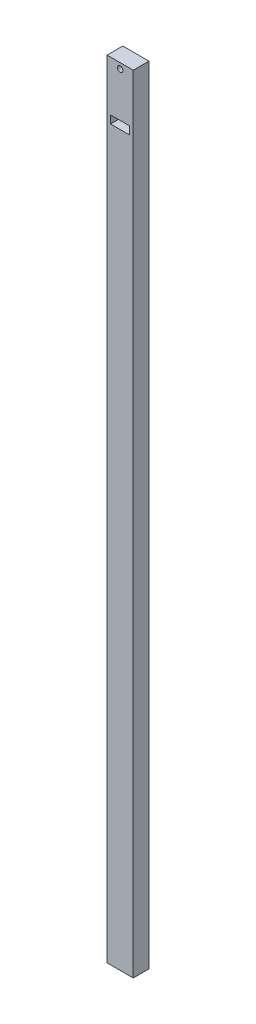
SolidWorks part; units mm, degrees
ref_plane "Front Plane" through (0, 0, 0) normal (0, 0, 1) x (1, 0, 0)
ref_plane "Top Plane" through (0, 0, 0) normal (0, 1, 0) x (1, 0, 0)
ref_plane "Right Plane" through (0, 0, 0) normal (1, 0, 0) x (0, 0, -1)
sketch "Sketch1" plane through (0, 0, 0) normal (0, 0, 1) x (1, 0, 0)
  line L0 (5, 0) -> (5, 300) construction
  line L1 (0, 0) -> (10, 0)
  line L2 (0, 0) -> (0, 300)
  line L3 (0, 300) -> (10, 300)
  line L4 (10, 0) -> (10, 300)
  line L6 (1.34, 280.9) -> (8.66, 280.9)
  line L7 (1.34, 280.9) -> (1.34, 277.9)
  line L9 (8.66, 280.9) -> (8.66, 277.9)
  line L10 (1.34, 299.5) -> (8.66, 299.5)
  line L12 (1.34, 277.9) -> (8.66, 277.9)
  circle A0 centre (5, 297.9) radius 1.06
  point P13 (5, 280.9)
  point P18 (5, 299.5)
  dimension "D3" = 3
  dimension "D5" = 2.12
  dimension "D1" = 10
  dimension "D2" = 300
  dimension "D4" = 7.32
  dimension "D6" = 21.6
  dimension "D7" = 0.5
  dimension "D8" = 2.1
  dimension "D9" = 17
extrude "Boss-Extrude1" add sketch "Sketch1" along normal blind 6
